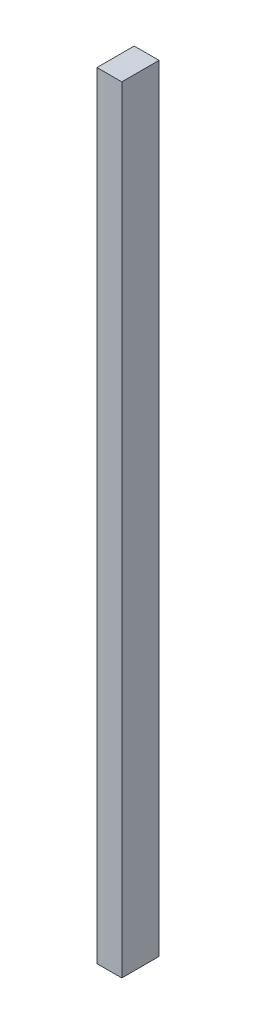
SolidWorks part; units mm, degrees
ref_plane "Front Plane" through (0, 0, 0) normal (0, 0, 1) x (1, 0, 0)
ref_plane "Top Plane" through (0, 0, 0) normal (0, 1, 0) x (1, 0, 0)
ref_plane "Right Plane" through (0, 0, 0) normal (1, 0, 0) x (0, 0, -1)
sketch "Sketch1" plane through (0, 0, 0) normal (0, 1, 0) x (1, 0, 0)
  line L1 (-4, -6) -> (4, -6)
  line L2 (-4, -6) -> (-4, 6)
  line L3 (-4, 6) -> (4, 6)
  line L4 (4, -6) -> (4, 6)
  line L5 (-4, -6) -> (4, 6) construction
  line L6 (-4, 6) -> (4, -6) construction
  point P0 (0, 0)
  dimension "D1" = 8
  dimension "D2" = 12
extrude "Boss-Extrude1" add sketch "Sketch1" along normal blind 250
